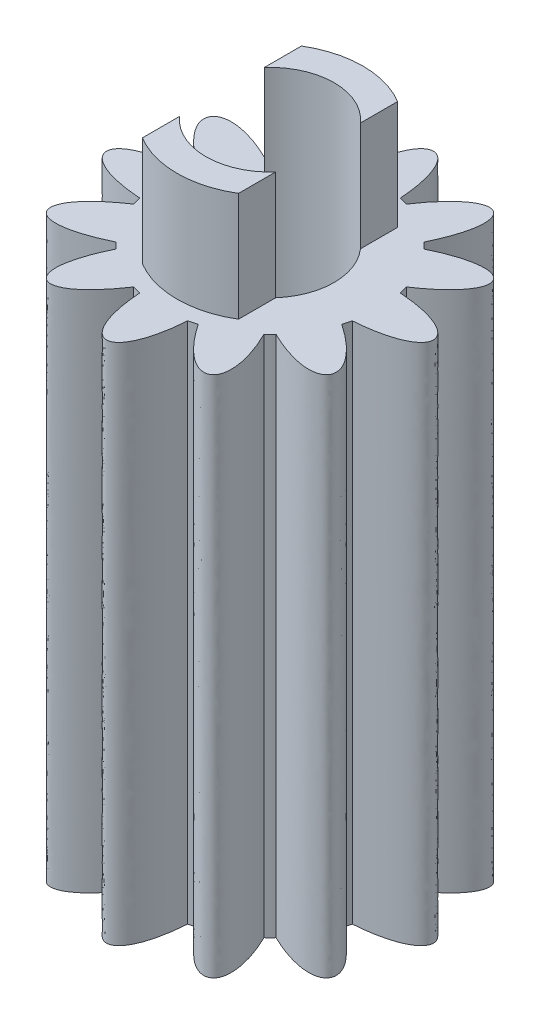
SolidWorks part; units mm, degrees
ref_plane "Front Plane" through (0, 0, 0) normal (0, 0, 1) x (1, 0, 0)
ref_plane "Top Plane" through (0, 0, 0) normal (0, 1, 0) x (1, 0, 0)
ref_plane "Right Plane" through (0, 0, 0) normal (1, 0, 0) x (0, 0, -1)
sketch "Sketch1" plane through (0, 0, 0) normal (0, 1, 0) x (1, 0, 0)
  line L0 (0, 0.0596) -> (0, 50000.0596) construction
  line L1 (0.75, -3.3162) -> (-0.75, -3.3162) construction
  line L2 (0.75, -3.3162) -> (0.75, 3.3162) construction
  line L3 (0.75, 3.3162) -> (-0.75, 3.3162) construction
  line L4 (-0.75, -3.3162) -> (-0.75, 3.3162) construction
  line L5 (0.75, -3.3162) -> (-0.75, 3.3162) construction
  line L6 (0.75, 3.3162) -> (-0.75, -3.3162) construction
  line L7 (0, 0) -> (0.75, 3.3162) construction
  circle A0 centre (0, 0) radius 3.4
  circle A1 centre (0, 0) radius 5.1 construction
  spline S0 degree 3 poles (-0.75, 3.3162) (-0.5833, 5.6946) (0.5833, 5.6946) (0.75, 3.3162) knots 0 0 0 0 1 1 1 1
  spline S1 degree 3 poles (1.0086, 3.247) (2.3421, 5.2233) (3.3525, 4.64) (2.3076, 2.497) knots 0 0 0 0 1 1 1 1
  spline S2 degree 3 poles (2.497, 2.3076) (4.64, 3.3525) (5.2233, 2.3421) (3.247, 1.0086) knots 0 0 0 0 1 1 1 1
  spline S3 degree 3 poles (3.3162, 0.75) (5.6946, 0.5833) (5.6946, -0.5833) (3.3162, -0.75) knots 0 0 0 0 1 1 1 1
  spline S4 degree 3 poles (3.247, -1.0086) (5.2233, -2.3421) (4.64, -3.3525) (2.497, -2.3076) knots 0 0 0 0 1 1 1 1
  spline S5 degree 3 poles (2.3076, -2.497) (3.3525, -4.64) (2.3421, -5.2233) (1.0086, -3.247) knots 0 0 0 0 1 1 1 1
  spline S6 degree 3 poles (0.75, -3.3162) (0.5833, -5.6946) (-0.5833, -5.6946) (-0.75, -3.3162) knots 0 0 0 0 1 1 1 1
  spline S7 degree 3 poles (-1.0086, -3.247) (-2.3421, -5.2233) (-3.3525, -4.64) (-2.3076, -2.497) knots 0 0 0 0 1 1 1 1
  spline S8 degree 3 poles (-2.497, -2.3076) (-4.64, -3.3525) (-5.2233, -2.3421) (-3.247, -1.0086) knots 0 0 0 0 1 1 1 1
  spline S9 degree 3 poles (-3.3162, -0.75) (-5.6946, -0.5833) (-5.6946, 0.5833) (-3.3162, 0.75) knots 0 0 0 0 1 1 1 1
  spline S10 degree 3 poles (-3.247, 1.0086) (-5.2233, 2.3421) (-4.64, 3.3525) (-2.497, 2.3076) knots 0 0 0 0 1 1 1 1
  spline S11 degree 3 poles (-2.3076, 2.497) (-3.3525, 4.64) (-2.3421, 5.2233) (-1.0086, 3.247) knots 0 0 0 0 1 1 1 1
  dimension "D1" = 6.8
  dimension "D2" = 10.2
  dimension "D3" = 1.5
  dimension "D4" = 3.4
extrude "Boss-Extrude1" add sketch "Sketch1" along normal blind 16.3 contours A0 | S9 A0 | S8 A0 | S7 A0 | S6 A0 | S5 A0 | S4 A0 | S3 A0 | S2 A0 | S1 A0 | S10 A0 | S11 A0 | S0 A0
sketch "Sketch4" plane through (0, 16.3, 0) normal (0, 1, 0) x (1, 0, 0)
  circle A0 centre (0, 0) radius 2.9
  dimension "D1" = 5.8
extrude "Boss-Extrude2" add sketch "Sketch4" along normal blind 3.4
sketch "Sketch2" plane through (0, 0, 0) normal (0, -1, 0) x (1, 0, 0)
  circle A0 centre (0, 0) radius 2
  dimension "D1" = 4
extrude "Cut-Extrude2" cut sketch "Sketch2" against normal blind 19.7
sketch "Sketch5" plane through (0, 16.3, 0) normal (0, 1, 0) x (1, 0, 0)
  line L1 (1.5, -6) -> (-1.5, -6) construction
  line L2 (1.5, -6) -> (1.5, 6) construction
  line L3 (1.5, 6) -> (-1.5, 6) construction
  line L4 (-1.5, -6) -> (-1.5, 6) construction
  line L5 (1.5, -6) -> (-1.5, 6) construction
  line L6 (1.5, 6) -> (-1.5, -6) construction
  line L7 (1.5, 6) -> (3.5, 6)
  line L8 (1.5, 6) -> (1.5, -6)
  line L9 (1.5, -6) -> (3.5, -6)
  line L10 (3.5, 6) -> (3.5, -6)
  line L11 (-1.5, 6) -> (-3.5, 6)
  line L12 (-1.5, 6) -> (-1.5, -6)
  line L13 (-1.5, -6) -> (-3.5, -6)
  line L14 (-3.5, 6) -> (-3.5, -6)
  point P0 (0, 0)
  dimension "D1" = 3
  dimension "D2" = 12
  dimension "D3" = 2
extrude "Cut-Extrude3" cut sketch "Sketch5" along normal up to surface (3.4 mm away) up to face at (0, 19.7, -2)
